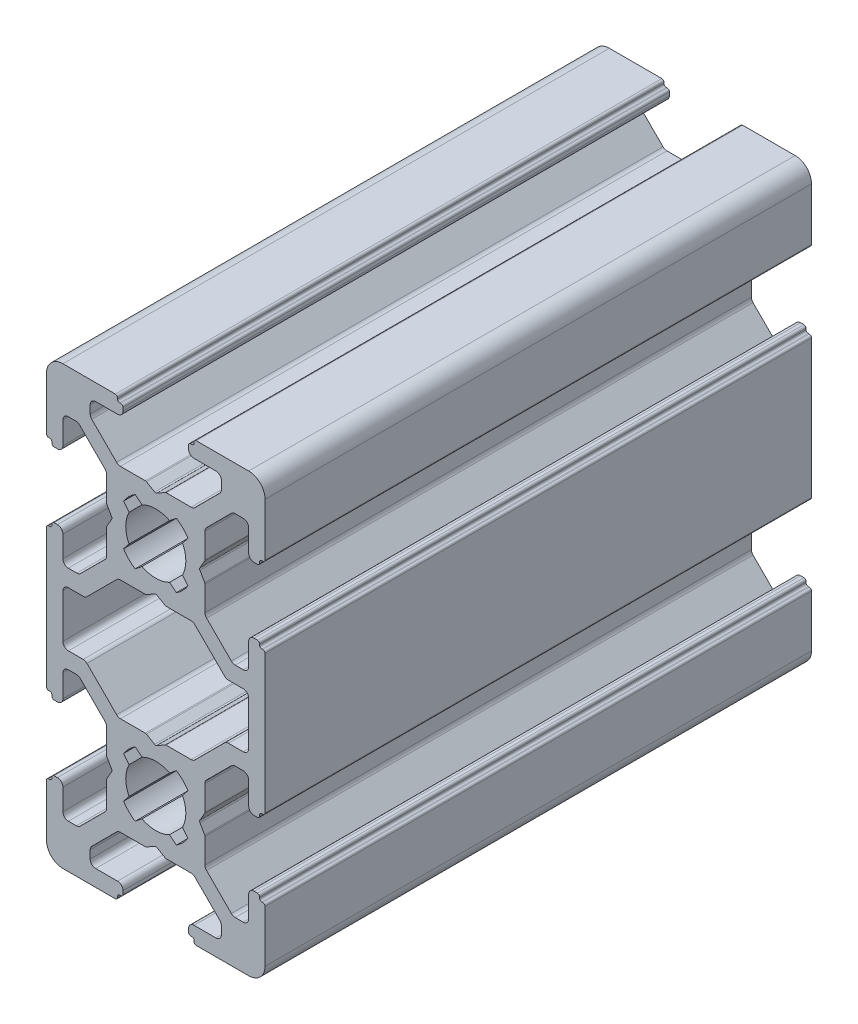
SolidWorks part; units mm, degrees
material "6061 Alloy"
ref_plane "Front Plane" through (0, 0, 0) normal (0, 0, 1) x (1, 0, 0)
ref_plane "Top Plane" through (0, 0, 0) normal (0, 1, 0) x (1, 0, 0)
ref_plane "Right Plane" through (0, 0, 0) normal (1, 0, 0) x (0, 0, -1)
sketch "Sketch1" plane through (0, 0, 0) normal (0, 0, 1) x (1, 0, 0)
  line L0 (10, -3.75) -> (10, -8.5)
  line L1 (8.5, -3.55) -> (8.5, -5.5)
  line L2 (9.5, -3.25) -> (9.5, -3.35)
  line L3 (9.7, -3.55) -> (9.8, -3.55)
  line L4 (9, -3.05) -> (9.3, -3.05)
  line L5 (9.7, 3.45) -> (9.8, 3.45)
  line L6 (9.5, 3.15) -> (9.5, 3.25)
  line L7 (9, 2.95) -> (9.3, 2.95)
  line L8 (8.5, 3.45) -> (8.5, 5.5)
  line L9 (10, 3.65) -> (10, 10)
  line L10 (-9.7, 3.45) -> (-9.8, 3.45)
  line L11 (-9.5, 3.15) -> (-9.5, 3.25)
  line L12 (-9, 2.95) -> (-9.3, 2.95)
  line L13 (-8.5, 3.45) -> (-8.5, 5.5)
  line L14 (-10, 3.65) -> (-10, 10)
  line L15 (-9.7, -3.55) -> (-9.8, -3.55)
  line L16 (-9.5, -3.25) -> (-9.5, -3.35)
  line L17 (-9, -3.05) -> (-9.3, -3.05)
  line L18 (-8.5, -3.55) -> (-8.5, -5.5)
  line L19 (-10, -3.75) -> (-10, -8.5)
  line L20 (-3.7, -10) -> (-8.5, -10)
  line L21 (-3.5, -8.5) -> (-5.5, -8.5)
  line L22 (-3.2, -9.5) -> (-3.3, -9.5)
  line L23 (-3.5, -9.7) -> (-3.5, -9.8)
  line L24 (-3, -9) -> (-3, -9.3)
  line L25 (3.7, -10) -> (8.5, -10)
  line L26 (3.5, -9.7) -> (3.5, -9.8)
  line L27 (3.2, -9.5) -> (3.3, -9.5)
  line L28 (3, -9) -> (3, -9.3)
  line L29 (3.5, -8.5) -> (5.5, -8.5)
  line L30 (-9.7, 23.5) -> (-9.8, 23.5)
  line L31 (-9.5, 23.2) -> (-9.5, 23.3)
  line L32 (-9, 23) -> (-9.3, 23)
  line L33 (-8.5, 23.5) -> (-8.5, 25.55)
  line L34 (-10, 23.7) -> (-10, 28.5)
  line L35 (-9.7, 16.5) -> (-9.8, 16.5)
  line L36 (-9.5, 16.8) -> (-9.5, 16.7)
  line L37 (-9, 17) -> (-9.3, 17)
  line L38 (-8.5, 16.5) -> (-8.5, 14.55)
  line L39 (-10, 16.3) -> (-10, 10)
  line L40 (10, 16.3) -> (10, 10)
  line L41 (8.5, 16.5) -> (8.5, 14.5)
  line L42 (9.5, 16.8) -> (9.5, 16.7)
  line L43 (9.7, 16.5) -> (9.8, 16.5)
  line L44 (9, 17) -> (9.3, 17)
  line L45 (9.7, 23.5) -> (9.8, 23.5)
  line L46 (9.5, 23.2) -> (9.5, 23.3)
  line L47 (9, 23) -> (9.3, 23)
  line L48 (8.5, 23.5) -> (8.5, 25.5)
  line L49 (10, 23.7) -> (10, 28.5)
  line L50 (-3.7, 30) -> (-8.5, 30)
  line L51 (-3.5, 28.5) -> (-5.5, 28.5)
  line L52 (-3, 29) -> (-3, 29.3)
  line L53 (-3.2, 29.5) -> (-3.3, 29.5)
  line L54 (-3.5, 29.7) -> (-3.5, 29.8)
  line L55 (3.7, 30) -> (8.5, 30)
  line L56 (3.5, 28.5) -> (5.5, 28.5)
  line L57 (3.2, 29.5) -> (3.3, 29.5)
  line L58 (3.5, 29.7) -> (3.5, 29.8)
  line L59 (3, 29) -> (3, 29.3)
  line L60 (2.4453, 18.7418) -> (2.9477, 18.1129)
  line L61 (1.2582, 17.5547) -> (1.8871, 17.0523)
  line L62 (-1.2582, 17.5547) -> (-1.8871, 17.0523)
  line L63 (-2.4453, 18.7418) -> (-2.9477, 18.1129)
  line L64 (-2.4453, 21.2582) -> (-2.9477, 21.8871)
  line L65 (-1.2582, 22.4453) -> (-1.8871, 22.9477)
  line L66 (3.5859, 24.6465) -> (5.8536, 26.9142)
  line L67 (4.6464, 23.5858) -> (6.9142, 25.8536)
  line L68 (4.5, 23.2322) -> (4.5, 20.9536)
  line L69 (4.4732, 20.8536) -> (4.0381, 20.1)
  line L70 (4.4732, 19.1464) -> (4.0381, 19.9)
  line L71 (4.5, 16.7678) -> (4.5, 19.0464)
  line L72 (7.2678, 26) -> (8, 26)
  line L73 (7.2678, 14) -> (8, 14)
  line L74 (2.4453, 21.2582) -> (2.9477, 21.8871)
  line L75 (4.6464, 16.4142) -> (6.9142, 14.1464)
  line L76 (3.2322, 15.5) -> (0.9536, 15.5)
  line L77 (0.8536, 15.5268) -> (0.1, 15.9619)
  line L78 (-0.8536, 15.5268) -> (-0.1, 15.9619)
  line L79 (-3.2322, 15.5) -> (-0.9536, 15.5)
  line L80 (3.5858, 15.3535) -> (6.2929, 12.6464)
  line L81 (-3.5858, 15.3535) -> (-6.2929, 12.6464)
  line L82 (-4.5, 16.7678) -> (-4.5, 19.0464)
  line L83 (-4.4732, 19.1464) -> (-4.0381, 19.9)
  line L84 (-4.4732, 20.8536) -> (-4.0381, 20.1)
  line L85 (-4.5, 23.2322) -> (-4.5, 20.9536)
  line L86 (-7.2178, 14.05) -> (-8, 14.05)
  line L87 (-7.3178, 26.05) -> (-8, 26.05)
  line L88 (-4.6464, 16.4142) -> (-6.8642, 14.1964)
  line L89 (-4.6464, 23.5858) -> (-6.9642, 25.9036)
  line L90 (1.2582, 22.4453) -> (1.8871, 22.9477)
  line L91 (-3.5859, 24.6465) -> (-5.8536, 26.9142)
  line L92 (6, 27.2678) -> (6, 28)
  line L93 (-6, 27.2678) -> (-6, 28)
  line L94 (3.2323, 24.5) -> (0.9537, 24.5)
  line L95 (0.8537, 24.4733) -> (0.1, 24.0381)
  line L96 (-0.8537, 24.4733) -> (-0.1, 24.0381)
  line L97 (-3.2323, 24.5) -> (-0.9537, 24.5)
  line L98 (-3.2322, -4.5) -> (-0.9536, -4.5)
  line L99 (-0.8536, -4.4732) -> (-0.1, -4.0381)
  line L100 (0.8536, -4.4732) -> (0.1, -4.0381)
  line L101 (3.2322, -4.5) -> (0.9536, -4.5)
  line L102 (-6, -7.2678) -> (-6, -8)
  line L103 (6, -7.2678) -> (6, -8)
  line L104 (-3.5858, -4.6464) -> (-5.8536, -6.9142)
  line L105 (1.2582, -2.4453) -> (1.8871, -2.9477)
  line L106 (-4.6464, -3.5858) -> (-6.9142, -5.8536)
  line L107 (-4.6464, 3.5858) -> (-6.9142, 5.8536)
  line L108 (-7.2678, -6) -> (-8, -6)
  line L109 (-7.2678, 6) -> (-8, 6)
  line L110 (-4.5, -3.2322) -> (-4.5, -0.9536)
  line L111 (-4.4732, -0.8536) -> (-4.0381, -0.1)
  line L112 (-4.4732, 0.8536) -> (-4.0381, 0.1)
  line L113 (-4.5, 3.2322) -> (-4.5, 0.9536)
  line L114 (-3.586, 4.6466) -> (-6.2929, 7.3535)
  line L115 (3.586, 4.6466) -> (6.2929, 7.3535)
  line L116 (-3.2324, 4.5001) -> (-0.9538, 4.5001)
  line L117 (-0.8538, 4.4733) -> (-0.1, 4.0381)
  line L118 (0.8538, 4.4733) -> (0.1, 4.0381)
  line L119 (3.2324, 4.5001) -> (0.9538, 4.5001)
  line L120 (4.6464, 3.5858) -> (6.9142, 5.8536)
  line L121 (2.4453, -1.2582) -> (2.9477, -1.8871)
  line L122 (7.2678, 6) -> (8, 6)
  line L123 (7.2678, -6) -> (8, -6)
  line L124 (4.5, 3.2322) -> (4.5, 0.9536)
  line L125 (4.4732, 0.8536) -> (4.0381, 0.1)
  line L126 (4.4732, -0.8536) -> (4.0381, -0.1)
  line L127 (4.5, -3.2322) -> (4.5, -0.9536)
  line L128 (4.6464, -3.5858) -> (6.9142, -5.8536)
  line L129 (3.5858, -4.6464) -> (5.8536, -6.9142)
  line L130 (-1.2582, -2.4453) -> (-1.8871, -2.9477)
  line L131 (-2.4453, -1.2582) -> (-2.9477, -1.8871)
  line L132 (-2.4453, 1.2582) -> (-2.9477, 1.8871)
  line L133 (-1.2582, 2.4453) -> (-1.8871, 2.9477)
  line L134 (1.2582, 2.4453) -> (1.8871, 2.9477)
  line L135 (2.4453, 1.2582) -> (2.9477, 1.8871)
  line L136 (6.6464, 12.5) -> (8, 12.5)
  line L137 (8.5, 8) -> (8.5, 12)
  line L138 (6.6464, 7.5) -> (8, 7.5)
  line L139 (-6.6464, 7.5) -> (-8, 7.5)
  line L140 (-8.5, 8) -> (-8.5, 12)
  line L141 (-6.6464, 12.5) -> (-8, 12.5)
  line L142 (0, 33.3296) -> (0, -13.4112) construction
  line L143 (-17.1897, 10) -> (16.9575, 10) construction
  line L144 (-17.1897, 0) -> (16.9575, 0) construction
  line L145 (-17.1897, 20) -> (16.9575, 20) construction
  arc A0 (9.5, -3.25) -> (9.3, -3.05) centre (9.3, -3.25) ccw
  arc A1 (10, -3.75) -> (9.8, -3.55) centre (9.8, -3.75) ccw
  arc A2 (9.5, -3.35) -> (9.7, -3.55) centre (9.7, -3.35) ccw
  arc A3 (9, -3.05) -> (8.5, -3.55) centre (9, -3.55) ccw
  arc A4 (9.7, 3.45) -> (9.5, 3.25) centre (9.7, 3.25) ccw
  arc A5 (9.8, 3.45) -> (10, 3.65) centre (9.8, 3.65) ccw
  arc A6 (9.3, 2.95) -> (9.5, 3.15) centre (9.3, 3.15) ccw
  arc A7 (8.5, 3.45) -> (9, 2.95) centre (9, 3.45) ccw
  arc A8 (-9.5, 3.25) -> (-9.7, 3.45) centre (-9.7, 3.25) ccw
  arc A9 (-10, 3.65) -> (-9.8, 3.45) centre (-9.8, 3.65) ccw
  arc A10 (-9.5, 3.15) -> (-9.3, 2.95) centre (-9.3, 3.15) ccw
  arc A11 (-9, 2.95) -> (-8.5, 3.45) centre (-9, 3.45) ccw
  arc A12 (-9.7, -3.55) -> (-9.5, -3.35) centre (-9.7, -3.35) ccw
  arc A13 (-9.8, -3.55) -> (-10, -3.75) centre (-9.8, -3.75) ccw
  arc A14 (-9.3, -3.05) -> (-9.5, -3.25) centre (-9.3, -3.25) ccw
  arc A15 (-8.5, -3.55) -> (-9, -3.05) centre (-9, -3.55) ccw
  arc A16 (-3.2, -9.5) -> (-3, -9.3) centre (-3.2, -9.3) ccw
  arc A17 (-3.7, -10) -> (-3.5, -9.8) centre (-3.7, -9.8) ccw
  arc A18 (-3.3, -9.5) -> (-3.5, -9.7) centre (-3.3, -9.7) ccw
  arc A19 (-3, -9) -> (-3.5, -8.5) centre (-3.5, -9) ccw
  arc A20 (3.5, -9.7) -> (3.3, -9.5) centre (3.3, -9.7) ccw
  arc A21 (3.5, -9.8) -> (3.7, -10) centre (3.7, -9.8) ccw
  arc A22 (3, -9.3) -> (3.2, -9.5) centre (3.2, -9.3) ccw
  arc A23 (3.5, -8.5) -> (3, -9) centre (3.5, -9) ccw
  arc A24 (-9.5, 23.3) -> (-9.7, 23.5) centre (-9.7, 23.3) ccw
  arc A25 (-10, 23.7) -> (-9.8, 23.5) centre (-9.8, 23.7) ccw
  arc A26 (-9.5, 23.2) -> (-9.3, 23) centre (-9.3, 23.2) ccw
  arc A27 (-9, 23) -> (-8.5, 23.5) centre (-9, 23.5) ccw
  arc A28 (-9.7, 16.5) -> (-9.5, 16.7) centre (-9.7, 16.7) ccw
  arc A29 (-9.8, 16.5) -> (-10, 16.3) centre (-9.8, 16.3) ccw
  arc A30 (-9.3, 17) -> (-9.5, 16.8) centre (-9.3, 16.8) ccw
  arc A31 (-8.5, 16.5) -> (-9, 17) centre (-9, 16.5) ccw
  arc A32 (9.5, 16.8) -> (9.3, 17) centre (9.3, 16.8) ccw
  arc A33 (10, 16.3) -> (9.8, 16.5) centre (9.8, 16.3) ccw
  arc A34 (9.5, 16.7) -> (9.7, 16.5) centre (9.7, 16.7) ccw
  arc A35 (9, 17) -> (8.5, 16.5) centre (9, 16.5) ccw
  arc A36 (9.7, 23.5) -> (9.5, 23.3) centre (9.7, 23.3) ccw
  arc A37 (9.8, 23.5) -> (10, 23.7) centre (9.8, 23.7) ccw
  arc A38 (9.3, 23) -> (9.5, 23.2) centre (9.3, 23.2) ccw
  arc A39 (8.5, 23.5) -> (9, 23) centre (9, 23.5) ccw
  arc A40 (-3, 29.3) -> (-3.2, 29.5) centre (-3.2, 29.3) ccw
  arc A41 (-3.5, 29.8) -> (-3.7, 30) centre (-3.7, 29.8) ccw
  arc A42 (-3.5, 29.7) -> (-3.3, 29.5) centre (-3.3, 29.7) ccw
  arc A43 (-3.5, 28.5) -> (-3, 29) centre (-3.5, 29) ccw
  arc A44 (3.2, 29.5) -> (3, 29.3) centre (3.2, 29.3) ccw
  arc A45 (3.7, 30) -> (3.5, 29.8) centre (3.7, 29.8) ccw
  arc A46 (3.3, 29.5) -> (3.5, 29.7) centre (3.3, 29.7) ccw
  arc A47 (3, 29) -> (3.5, 28.5) centre (3.5, 29) ccw
  arc A48 (2.4453, 18.7418) -> (2.4453, 21.2582) centre (0, 20) ccw
  arc A49 (-1.2582, 17.5547) -> (1.2582, 17.5547) centre (0, 20) ccw
  arc A50 (-2.4453, 21.2582) -> (-2.4453, 18.7418) centre (0, 20) ccw
  arc A51 (1.8871, 17.0523) -> (2.9477, 18.1129) centre (0, 20) ccw
  arc A52 (-2.9477, 18.1129) -> (-1.8871, 17.0523) centre (0, 20) ccw
  arc A53 (-1.8871, 22.9477) -> (-2.9477, 21.8871) centre (0, 20) ccw
  arc A54 (2.9477, 21.8871) -> (1.8871, 22.9477) centre (0, 20) ccw
  arc A55 (4.0381, 20.1) -> (4.0381, 19.9) centre (4.2113, 20) ccw
  arc A56 (4.5, 19.0464) -> (4.4732, 19.1464) centre (4.3, 19.0464) ccw
  arc A57 (4.4732, 20.8536) -> (4.5, 20.9536) centre (4.3, 20.9536) ccw
  arc A58 (6.9142, 14.1464) -> (7.2678, 14) centre (7.2678, 14.5) ccw
  arc A59 (4.5, 16.7678) -> (4.6464, 16.4142) centre (5, 16.7678) ccw
  arc A60 (4.6464, 23.5858) -> (4.5, 23.2322) centre (5, 23.2322) ccw
  arc A61 (7.2678, 26) -> (6.9142, 25.8536) centre (7.2678, 25.5) ccw
  arc A62 (0.1, 15.9619) -> (-0.1, 15.9619) centre (0, 15.7887) ccw
  arc A63 (-0.9536, 15.5) -> (-0.8536, 15.5268) centre (-0.9536, 15.7) ccw
  arc A64 (0.8536, 15.5268) -> (0.9536, 15.5) centre (0.9536, 15.7) ccw
  arc A65 (-3.2322, 15.5) -> (-3.5858, 15.3535) centre (-3.2322, 15) ccw
  arc A66 (3.5858, 15.3535) -> (3.2322, 15.5) centre (3.2322, 15) ccw
  arc A67 (-4.0381, 19.9) -> (-4.0381, 20.1) centre (-4.2113, 20) ccw
  arc A68 (-4.5, 20.9536) -> (-4.4732, 20.8536) centre (-4.3, 20.9536) ccw
  arc A69 (-4.4732, 19.1464) -> (-4.5, 19.0464) centre (-4.3, 19.0464) ccw
  arc A70 (-6.9642, 25.9036) -> (-7.3178, 26.05) centre (-7.3178, 25.55) ccw
  arc A71 (-4.5, 23.2322) -> (-4.6464, 23.5858) centre (-5, 23.2322) ccw
  arc A72 (-4.6464, 16.4142) -> (-4.5, 16.7678) centre (-5, 16.7678) ccw
  arc A73 (-7.2178, 14.05) -> (-6.8642, 14.1964) centre (-7.2178, 14.55) ccw
  arc A74 (-6, 27.2678) -> (-5.8536, 26.9142) centre (-5.5, 27.2678) ccw
  arc A75 (-3.5859, 24.6465) -> (-3.2323, 24.5) centre (-3.2323, 25) ccw
  arc A76 (3.2323, 24.5) -> (3.5859, 24.6465) centre (3.2323, 25) ccw
  arc A77 (5.8536, 26.9142) -> (6, 27.2678) centre (5.5, 27.2678) ccw
  arc A78 (8.5, 25.5) -> (8, 26) centre (8, 25.5) ccw
  arc A79 (10, 28.5) -> (8.5, 30) centre (8.5, 28.5) ccw
  arc A80 (8, 14) -> (8.5, 14.5) centre (8, 14.5) ccw
  arc A81 (-8.5, 14.55) -> (-8, 14.05) centre (-8, 14.55) ccw
  arc A82 (-8, 26.05) -> (-8.5, 25.55) centre (-8, 25.55) ccw
  arc A83 (6, 28) -> (5.5, 28.5) centre (5.5, 28) ccw
  arc A84 (-8.5, 30) -> (-10, 28.5) centre (-8.5, 28.5) ccw
  arc A85 (-5.5, 28.5) -> (-6, 28) centre (-5.5, 28) ccw
  arc A86 (-0.8537, 24.4733) -> (-0.9537, 24.5) centre (-0.9537, 24.3) ccw
  arc A87 (0.9537, 24.5) -> (0.8537, 24.4733) centre (0.9537, 24.3) ccw
  arc A88 (-0.1, 24.0381) -> (0.1, 24.0381) centre (0, 24.2113) ccw
  arc A89 (1.2582, 22.4453) -> (-1.2582, 22.4453) centre (0, 20) ccw
  arc A90 (-1.2582, -2.4453) -> (1.2582, -2.4453) centre (0, 0) ccw
  arc A91 (0.1, -4.0381) -> (-0.1, -4.0381) centre (0, -4.2113) ccw
  arc A92 (0.8536, -4.4732) -> (0.9536, -4.5) centre (0.9536, -4.3) ccw
  arc A93 (-0.9536, -4.5) -> (-0.8536, -4.4732) centre (-0.9536, -4.3) ccw
  arc A94 (-6, -8) -> (-5.5, -8.5) centre (-5.5, -8) ccw
  arc A95 (-10, -8.5) -> (-8.5, -10) centre (-8.5, -8.5) ccw
  arc A96 (5.5, -8.5) -> (6, -8) centre (5.5, -8) ccw
  arc A97 (-8.5, -5.5) -> (-8, -6) centre (-8, -5.5) ccw
  arc A98 (-8, 6) -> (-8.5, 5.5) centre (-8, 5.5) ccw
  arc A99 (8.5, 5.5) -> (8, 6) centre (8, 5.5) ccw
  arc A100 (8.5, -10) -> (10, -8.5) centre (8.5, -8.5) ccw
  arc A101 (8, -6) -> (8.5, -5.5) centre (8, -5.5) ccw
  arc A102 (6, -7.2678) -> (5.8536, -6.9142) centre (5.5, -7.2678) ccw
  arc A103 (3.5858, -4.6464) -> (3.2322, -4.5) centre (3.2322, -5) ccw
  arc A104 (-3.2322, -4.5) -> (-3.5858, -4.6464) centre (-3.2322, -5) ccw
  arc A105 (-5.8536, -6.9142) -> (-6, -7.2678) centre (-5.5, -7.2678) ccw
  arc A106 (-6.9142, 5.8536) -> (-7.2678, 6) centre (-7.2678, 5.5) ccw
  arc A107 (-4.5, 3.2322) -> (-4.6464, 3.5858) centre (-5, 3.2322) ccw
  arc A108 (-4.6464, -3.5858) -> (-4.5, -3.2322) centre (-5, -3.2322) ccw
  arc A109 (-7.2678, -6) -> (-6.9142, -5.8536) centre (-7.2678, -5.5) ccw
  arc A110 (-4.5, 0.9536) -> (-4.4732, 0.8536) centre (-4.3, 0.9536) ccw
  arc A111 (-4.4732, -0.8536) -> (-4.5, -0.9536) centre (-4.3, -0.9536) ccw
  arc A112 (-4.0381, -0.1) -> (-4.0381, 0.1) centre (-4.2113, 0) ccw
  arc A113 (3.2324, 4.5001) -> (3.586, 4.6466) centre (3.2324, 5.0001) ccw
  arc A114 (-3.586, 4.6466) -> (-3.2324, 4.5001) centre (-3.2324, 5.0001) ccw
  arc A115 (0.9538, 4.5001) -> (0.8538, 4.4733) centre (0.9538, 4.3001) ccw
  arc A116 (-0.8538, 4.4733) -> (-0.9538, 4.5001) centre (-0.9538, 4.3001) ccw
  arc A117 (-0.1, 4.0381) -> (0.1, 4.0381) centre (0, 4.2113) ccw
  arc A118 (6.9142, -5.8536) -> (7.2678, -6) centre (7.2678, -5.5) ccw
  arc A119 (4.5, -3.2322) -> (4.6464, -3.5858) centre (5, -3.2322) ccw
  arc A120 (4.6464, 3.5858) -> (4.5, 3.2322) centre (5, 3.2322) ccw
  arc A121 (7.2678, 6) -> (6.9142, 5.8536) centre (7.2678, 5.5) ccw
  arc A122 (4.5, -0.9536) -> (4.4732, -0.8536) centre (4.3, -0.9536) ccw
  arc A123 (4.4732, 0.8536) -> (4.5, 0.9536) centre (4.3, 0.9536) ccw
  arc A124 (4.0381, 0.1) -> (4.0381, -0.1) centre (4.2113, 0) ccw
  arc A125 (1.8871, -2.9477) -> (2.9477, -1.8871) centre (0, 0) ccw
  arc A126 (-2.9477, -1.8871) -> (-1.8871, -2.9477) centre (0, 0) ccw
  arc A127 (-1.8871, 2.9477) -> (-2.9477, 1.8871) centre (0, 0) ccw
  arc A128 (2.9477, 1.8871) -> (1.8871, 2.9477) centre (0, 0) ccw
  arc A129 (-2.4453, 1.2582) -> (-2.4453, -1.2582) centre (0, 0) ccw
  arc A130 (1.2582, 2.4453) -> (-1.2582, 2.4453) centre (0, 0) ccw
  arc A131 (2.4453, -1.2582) -> (2.4453, 1.2582) centre (0, 0) ccw
  arc A132 (-6.6464, 12.5) -> (-6.2929, 12.6464) centre (-6.6464, 13) ccw
  arc A133 (-8, 12.5) -> (-8.5, 12) centre (-8, 12) ccw
  arc A134 (-8.5, 8) -> (-8, 7.5) centre (-8, 8) ccw
  arc A135 (-6.2929, 7.3535) -> (-6.6464, 7.5) centre (-6.6464, 7) ccw
  arc A136 (6.2929, 12.6464) -> (6.6464, 12.5) centre (6.6464, 13) ccw
  arc A137 (8.5, 12) -> (8, 12.5) centre (8, 12) ccw
  arc A138 (8, 7.5) -> (8.5, 8) centre (8, 8) ccw
  arc A139 (6.6464, 7.5) -> (6.2929, 7.3535) centre (6.6464, 7) ccw
  dimension "D3" = 5.5
  dimension "D4" = 40
  dimension "D2" = 20
  dimension "D5" = 10
  dimension "D6" = 20
  dimension "D7" = 6
  dimension "D8" = 6
  dimension "D9" = 6
  dimension "D10" = 10
  dimension "D11" = 12
  dimension "D12" = 12
  dimension "D13" = 12
  dimension "D14" = 12
  dimension "D15" = 12
  dimension "D16" = 12
extrude "Extrude1" add sketch "Sketch1" along normal blind 50
